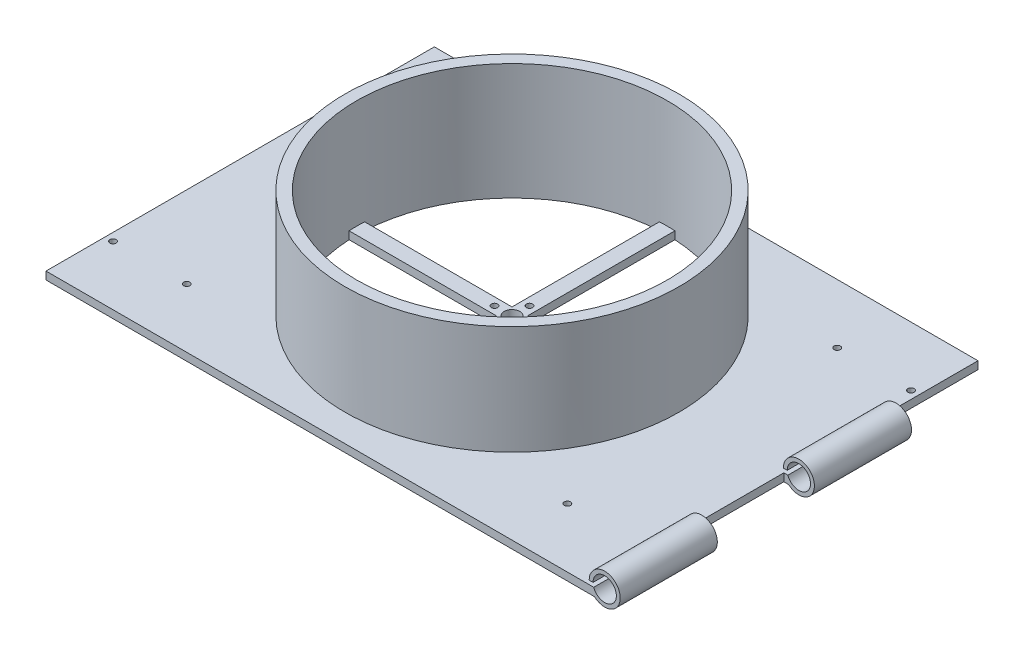
SolidWorks part; units mm, degrees
ref_plane "Alzado" through (0, 0, 0) normal (0, 0, 1) x (1, 0, 0)
ref_plane "Planta" through (0, 0, 0) normal (0, 1, 0) x (1, 0, 0)
ref_plane "Vista lateral" through (0, 0, 0) normal (1, 0, 0) x (0, 0, -1)
sketch "Croquis1" plane through (0, 0, 0) normal (0, 1, 0) x (1, 0, 0)
  circle A0 centre (0, 0) radius 40
  circle A1 centre (0, 0) radius 43
  point P7 (0, 0)
  point P10 (0, 0)
  dimension "D1" = 80
  dimension "D2" = 3
extrude "Saliente-Extruir1" add sketch "Croquis1" along normal blind 30 contours A1 A0
sketch "Croquis3" plane through (0, 0, 0) normal (0, 1, 0) x (1, 0, 0)
  line L1 (0, -40) -> (0, 40) construction
  line L8 (-40, 0) -> (40, 0) construction
  line L13 (-2, 2) -> (-2, 39.95)
  line L18 (-2, -39.95) -> (-2, -2)
  line L20 (2, -39.95) -> (2, -2)
  line L22 (-1.9287, -39.9535) -> (1.9287, 39.9535) construction
  line L23 (-1.9287, 39.9535) -> (1.9287, -39.9535) construction
  line L24 (-39.95, -2) -> (-2, -2)
  line L27 (-39.95, 2) -> (-2, 2)
  line L29 (-39.9548, -1.9002) -> (39.9548, 1.9002) construction
  line L30 (-39.9548, 1.9002) -> (39.9548, -1.9002) construction
  line L31 (2, 2) -> (39.95, 2)
  line L32 (2, 2) -> (2, 39.95)
  line L33 (2, -2) -> (39.95, -2)
  circle A0 centre (0, 0) radius 40 construction
  circle A1 centre (0, 0) radius 40
  circle A2 centre (0, 0) radius 2
  circle A3 centre (4.5, 0) radius 0.81
  circle A9 centre (-4.5, 0) radius 0.81
  circle A11 centre (0, -4.5) radius 0.81
  circle A12 centre (0, 4.5) radius 0.81
  dimension "D3" = 1.62
  dimension "D4" = 4.5
  dimension "D5" = 1.62
  dimension "D1" = 4
  dimension "D2" = 4
  dimension "D6" = 4.5
extrude "Saliente-Extruir2" add sketch "Croquis3" along normal blind 2
sketch "Croquis4" plane through (0, 0, 0) normal (0, 1, 0) x (1, 0, 0)
  line L0 (0, 0) -> (43, 0) construction
  line L5 (-70, -50) -> (70, -50)
  line L6 (-70, -50) -> (-70, 50)
  line L7 (-70, 50) -> (70, 50)
  line L8 (70, -50) -> (70, 50)
  line L9 (-70, -50) -> (70, 50) construction
  line L10 (-70, 50) -> (70, -50) construction
  circle A0 centre (0, 0) radius 43 construction
  circle A1 centre (0, 0) radius 43
  point P0 (0, 0)
  point P1 (0, 0)
  dimension "D1" = 70
  dimension "D3" = 43
  dimension "D2" = 50
  dimension "D4" = 27
extrude "Saliente-Extruir3" add sketch "Croquis4" along normal blind 2
sketch "Croquis5" plane through (0, 2, 0) normal (0, 1, 0) x (1, 0, 0)
  line L1 (-70, 50) -> (-70, -50) construction
  line L3 (0, 0) -> (38.3261, 0) construction
  line L5 (0, 0) -> (0, 15.249) construction
  line L6 (-70, -50) -> (70, -50) construction
  circle A4 centre (-68, -34.75) radius 0.81
  circle A12 centre (-49, -34.75) radius 0.81
  circle A13 centre (-49, 34.75) radius 0.81
  circle A14 centre (-68, 34.75) radius 0.81
  circle A15 centre (68, 34.75) radius 0.81
  circle A16 centre (49, 34.75) radius 0.81
  circle A17 centre (49, -34.75) radius 0.81
  circle A18 centre (68, -34.75) radius 0.81
  point P26 (0, 0)
  point P27 (0, 0)
  point P28 (0, 0)
  dimension "D1" = 1.62
  dimension "D3" = 2
  dimension "D5" = 19
  dimension "D4" = 15.25
extrude "Cortar-Extruir1" cut sketch "Croquis5" against normal blind 2
ref_plane "Plano1" through (0, 0, 50) normal (0, 0, 1) x (1, 0, 0)
sketch "Croquis7" plane through (0, 0, 50) normal (0, 0, 1) x (1, 0, 0)
  line L0 (70, 0) -> (69.981, 2.0767)
  line L1 (-70, 0) -> (70, 0) construction
  line L2 (70.873, 3) -> (69.873, 3)
  line L3 (70, 2) -> (71.0446, 2)
  line L4 (70, 0) -> (70, 2)
  line L5 (70, 0) -> (71.2272, 0)
  arc A1 (69.981, 2.0767) -> (70, 2) centre (73.873, 3) ccw
  arc A3 (71.0446, 2) -> (70.873, 3) centre (73.873, 3) ccw
  arc A4 (71.2272, 0) -> (69.873, 3) centre (73.873, 3) ccw
  dimension "D1" = 8
  dimension "D2" = 6
  dimension "D3" = 3
extrude "Saliente-Extruir7" add sketch "Croquis7" against normal blind 25 contours A3 L3 A1 L2
pattern_linear "MatrizL1" count 2 spacing 50 along (0, 0, -1) of "Saliente-Extruir7"
